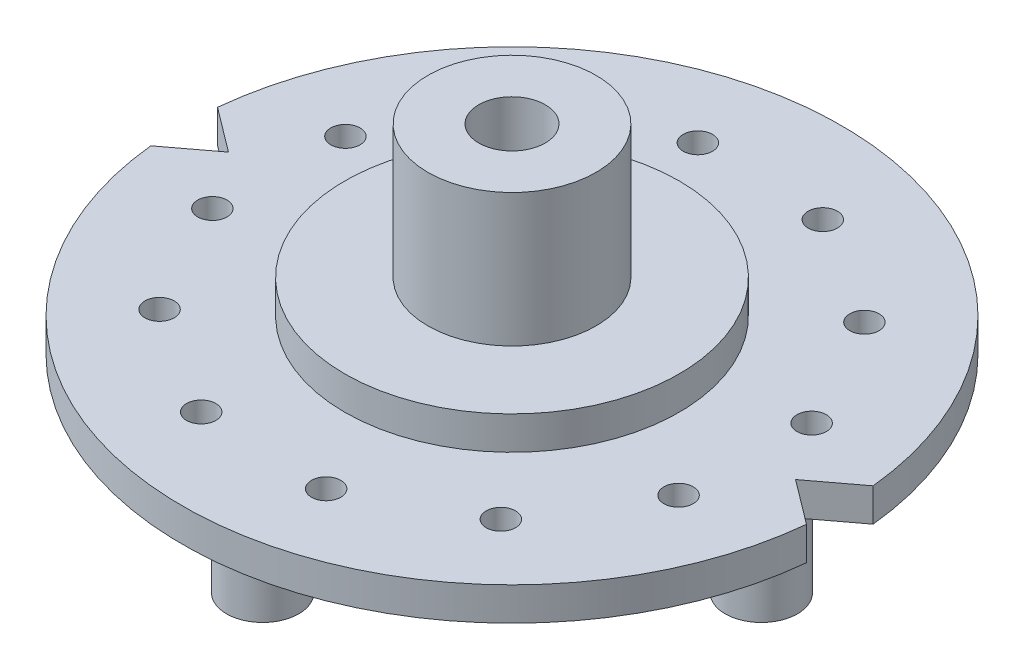
SolidWorks part; units mm, degrees
ref_plane "Front Plane" through (0, 0, 0) normal (0, 0, 1) x (1, 0, 0)
ref_plane "Top Plane" through (0, 0, 0) normal (0, 1, 0) x (1, 0, 0)
ref_plane "Right Plane" through (0, 0, 0) normal (1, 0, 0) x (0, 0, -1)
sketch "Sketch1" plane through (0, 0, 0) normal (0, 0, 1) x (1, 0, 0)
  line L0 (0, 0) -> (-42.799, 0)
  line L1 (-42.799, 0) -> (-42.799, 4.318)
  line L2 (-42.799, 4.318) -> (-21.717, 4.318)
  line L3 (-21.717, 4.318) -> (-21.717, 8.636)
  line L4 (-21.717, 8.636) -> (-10.922, 8.636)
  line L5 (-10.922, 8.636) -> (-10.922, 25.908)
  line L6 (-10.922, 25.908) -> (0, 25.908)
  line L7 (0, 25.908) -> (0, 0)
  line L8 (0, 25.908) -> (0, -23.737) construction
  line L10 (0, 25.908) -> (-4.318, 25.908)
  line L11 (0, 25.908) -> (0, 4.572)
  line L12 (0, 4.572) -> (-4.318, 4.572)
  line L13 (-4.318, 25.908) -> (-4.318, 4.572)
  dimension "D1" = 4.318
  dimension "D2" = 17.272
  dimension "D3" = 4.318
  dimension "D4" = 21.844
  dimension "D5" = 43.434
  dimension "D6" = 85.598
  dimension "D7" = 8.636
  dimension "D8" = 21.336
revolve "Revolve1" add sketch "Sketch1" angle 360 about L8
sketch "Sketch2" plane through (0, 4.318, 0) normal (0, 1, 0) x (1, 0, 0)
  circle A0 centre (-31.0011, 9.366) radius 1.905
  circle A1 centre (-22.1647, 23.6118) radius 1.905
  circle A2 centre (-7.3893, 31.5307) radius 1.905
  circle A3 centre (9.366, 31.0011) radius 1.905
  circle A4 centre (23.6118, 22.1647) radius 1.905
  circle A5 centre (31.5307, 7.3893) radius 1.905
  circle A6 centre (31.0011, -9.366) radius 1.905
  circle A7 centre (22.1647, -23.6118) radius 1.905
  circle A8 centre (7.3893, -31.5307) radius 1.905
  circle A9 centre (-9.366, -31.0011) radius 1.905
  circle A10 centre (-23.6118, -22.1647) radius 1.905
  circle A11 centre (-31.5307, -7.3893) radius 1.905
  point P28 (0, 0)
  dimension "D2" = 3.81
  dimension "D1" = 32.385
  dimension "D3" = 12
extrude "Cut-Extrude1" cut sketch "Sketch2" against normal up to vertex (4.318 mm away) up to point (0, 0, 0)
sketch "Sketch3" plane through (0, 0, 0) normal (0, -1, 0) x (1, 0, 0)
  line L0 (0, 42.799) -> (0, -45.0258) construction
  line L1 (42.5792, 4.3323) -> (36.83, 0)
  line L2 (-42.5792, 4.3323) -> (-36.83, 0)
  line L3 (36.83, 0) -> (42.5792, -4.3323)
  line L4 (-36.83, 0) -> (-42.5792, -4.3323)
  line L5 (0, 0) -> (82.4219, 0) construction
  circle A0 centre (0, 0) radius 42.799 construction
  arc A1 (0, 42.799) -> (0, -42.799) centre (0, 0) ccw
  arc A2 (42.5792, -4.3323) -> (42.5792, 4.3323) centre (0, 0) ccw
  point P2 (0, 0)
  point P13 (0, 0)
  circle M14 centre (0, 0) radius 42.799
  dimension "D1" = 74
  dimension "D2" = 36.83
extrude "Cut-Extrude2" cut sketch "Sketch3" against normal through all contours L1 L3 M14 | L4 L2 M14
sketch "Sketch4" plane through (0, 0, 0) normal (0, -1, 0) x (1, 0, 0)
  line L0 (-51.9571, 0) -> (65.9326, 0) construction
  circle A0 centre (0, 32.385) radius 4.699
  circle A1 centre (32.385, 0) radius 4.699
  circle A2 centre (0, -32.385) radius 4.699
  circle A3 centre (-32.385, 0) radius 4.699
  point P14 (0, 0)
  dimension "D2" = 9.398
  dimension "D1" = 32.385
  dimension "D3" = 4
extrude "Boss-Extrude1" add sketch "Sketch4" along normal blind 10.668
